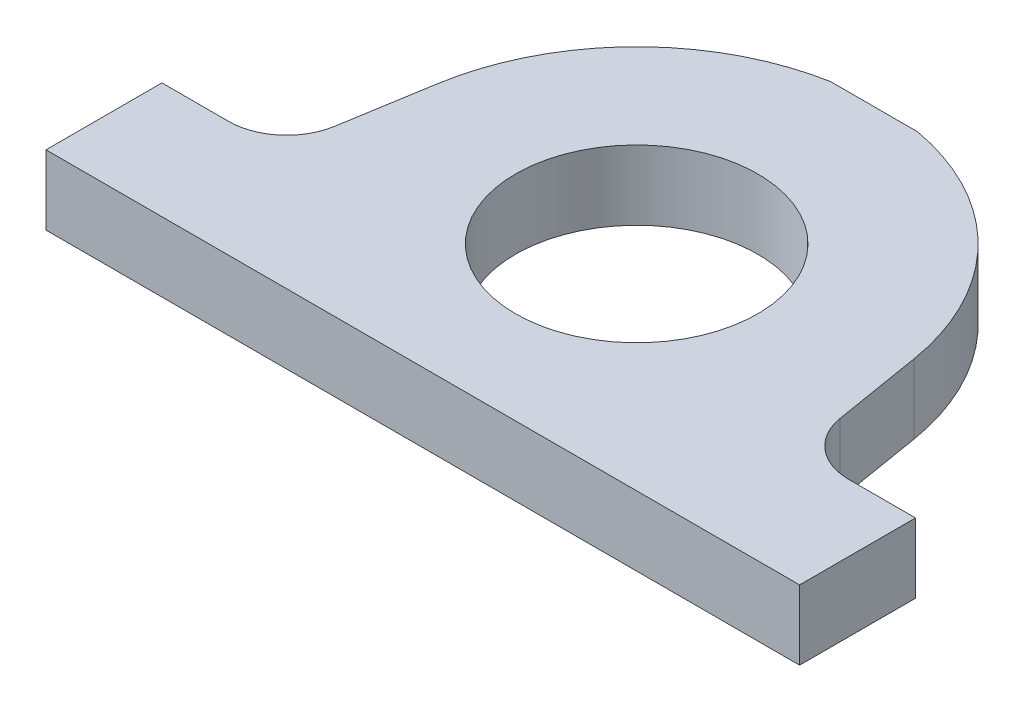
SolidWorks part; units mm, degrees
material "Acrylic (Medium-high impact)"
ref_plane "Front Plane" through (0, 0, 0) normal (0, 0, 1) x (1, 0, 0)
ref_plane "Top Plane" through (0, 0, 0) normal (0, 1, 0) x (1, 0, 0)
ref_plane "Right Plane" through (0, 0, 0) normal (1, 0, 0) x (0, 0, -1)
sketch "Sketch1" plane through (0, 0, 0) normal (0, 1, 0) x (1, 0, 0)
  line L0 (-41.0948, 6.7778) -> (-45, -16.9)
  line L1 (-65, -16.9) -> (-45, -16.9)
  line L3 (-65, -36.9) -> (65, -36.9)
  line L5 (41.0948, 6.7778) -> (45, -16.9)
  line L6 (0, -20.9) -> (0, -36.9) construction
  line L7 (45, -16.9) -> (65, -16.9)
  line L10 (65, -16.9) -> (65, -36.9)
  line L11 (-65, -16.9) -> (-65, -36.9)
  circle A0 centre (0, 0) radius 20.9
  arc A1 (41.0948, 6.7778) -> (-41.0948, 6.7778) centre (0, 0) ccw
  circle A3 centre (0, 0) radius 41.65 construction
  point P11 (27.5, 0)
  dimension "D1" = 41.8
  dimension "D3" = 16
  dimension "D4" = 130
  dimension "D5" = 20
  dimension "D6" = 20
  dimension "D2" = 20.75
extrude "Boss-Extrude1" add sketch "Sketch1" along normal blind 12
sketch "Sketch2" plane through (0, 0, 16.9) normal (0, 0, -1) x (-1, 0, 0)
  line L0 (-65, 12) -> (-45, 0) construction
  circle A0 centre (-55, 6) radius 1
  dimension "D1" = 2
extrude "Cut-Extrude1" cut sketch "Sketch2" against normal blind 3
sketch "Sketch3" plane through (0, 0, 16.9) normal (0, 0, -1) x (-1, 0, 0)
  line L0 (45, 12) -> (65, 0) construction
  circle A0 centre (55, 6) radius 1
  dimension "D1" = 2
extrude "Cut-Extrude2" cut sketch "Sketch3" against normal blind 3
sketch "Sketch4" plane through (0, 0, 0) normal (0, -1, 0) x (1, 0, 0)
  line L1 (7.5, -44.9579) -> (-7.5, -44.9579)
  line L2 (7.5, -44.9579) -> (7.5, -40.9692)
  line L3 (7.5, -40.9692) -> (-7.5, -40.9692)
  line L4 (-7.5, -44.9579) -> (-7.5, -40.9692)
  line L5 (7.5, -44.9579) -> (-7.5, -40.9692) construction
  line L6 (7.5, -40.9692) -> (-7.5, -44.9579) construction
  arc A1 (-41.0948, -6.7778) -> (41.0948, -6.7778) centre (0, 0) ccw construction
  point P0 (0, -42.9635)
  dimension "D1" = 15
fillet "Fillet1" radius 10 2 edges at (45, 6, 16.9) (-45, 6, 16.9)
extrude "Cut-Extrude3" cut sketch "Sketch4" against normal through all
sketch "Sketch8" plane through (0, 0, -40.9692) normal (0, 0, -1) x (-1, 0, 0)
  line L0 (-7.5, 12) -> (7.5, -4) construction
  line L1 (7.5, 12) -> (7.5, 0) construction
  circle A0 centre (0, 4) radius 1
  dimension "D2" = 2
  dimension "D1" = 16
extrude "Cut-Extrude4" cut sketch "Sketch8" against normal blind 2
